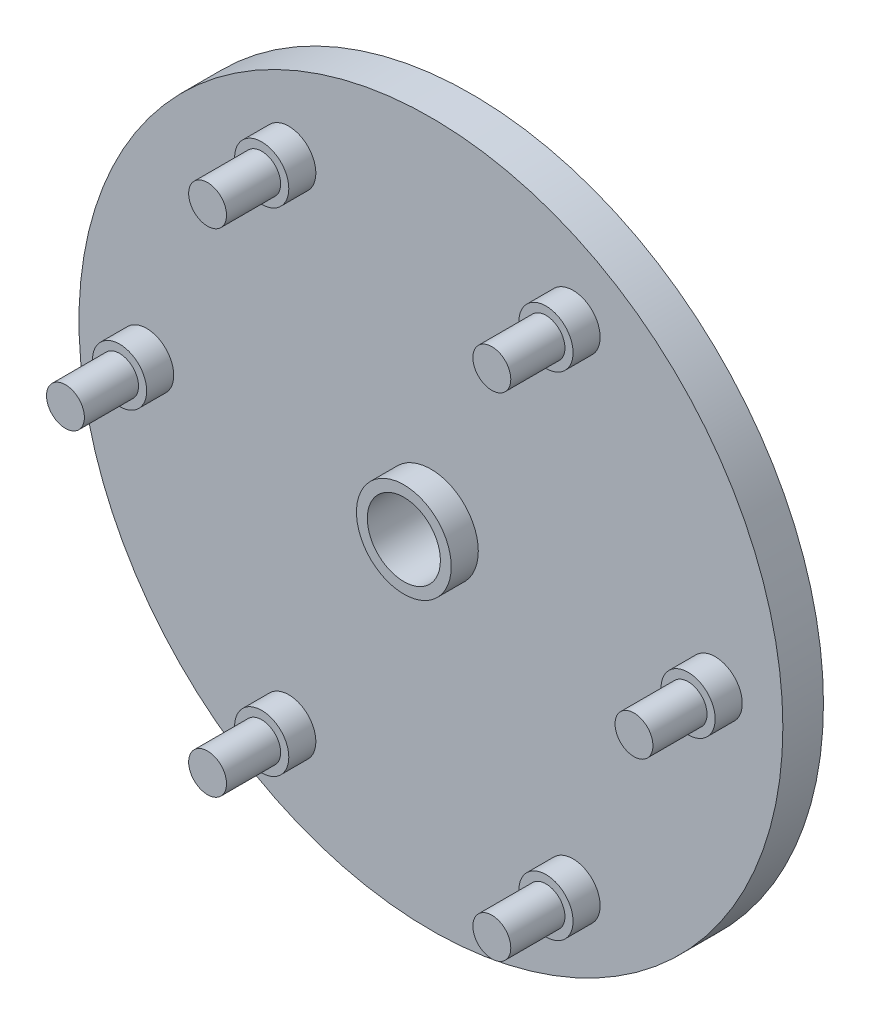
SolidWorks part; units mm, degrees
ref_plane "前视基准面" through (0, 0, 0) normal (0, 0, 1) x (1, 0, 0)
ref_plane "上视基准面" through (0, 0, 0) normal (0, 1, 0) x (1, 0, 0)
ref_plane "右视基准面" through (0, 0, 0) normal (1, 0, 0) x (0, 0, -1)
other "Configuration Table"
sketch "草图1" plane through (0, 0, 0) normal (0, 0, 1) x (1, 0, 0)
  circle A0 centre (0, 0) radius 26
  point P0 (0, 0)
  point P19 (0, 0)
  dimension "D1" = 52
extrude "凸台-拉伸1" add sketch "草图1" against normal blind 3 contours A0
sketch "草图2" plane through (0, 0, 0) normal (0, 0, 1) x (1, 0, 0)
  line L0 (0, 0) -> (-21, 0) construction
  circle A1 centre (-21, 0) radius 1.4
  circle A2 centre (-10.5, 18.1865) radius 1.4
  circle A3 centre (10.5, 18.1865) radius 1.4
  circle A4 centre (21, 0) radius 1.4
  circle A5 centre (10.5, -18.1865) radius 1.4
  circle A6 centre (-10.5, -18.1865) radius 1.4
  point P17 (0, 0)
  dimension "D1" = 2.8
  dimension "D2" = 21
  dimension "D3" = 6
extrude "凸台-拉伸2" add sketch "草图2" along normal blind 6
sketch "草图3" plane through (0, 0, 0) normal (0, 0, 1) x (1, 0, 0)
  circle A0 centre (0, 0) radius 7.5
  dimension "D1" = 15
extrude "凸台-拉伸3" [suppressed] add sketch "草图3" along normal blind 6
sketch "草图4" plane through (0, 0, 0) normal (0, 0, 1) x (1, 0, 0)
  circle A0 centre (-10.5, 18.1865) radius 2
  circle A1 centre (10.5, 18.1865) radius 2
  circle A2 centre (21, 0) radius 2
  circle A3 centre (10.5, -18.1865) radius 2
  circle A4 centre (-10.5, -18.1865) radius 2
  circle A5 centre (-21, 0) radius 2
  point P16 (0, 0)
  dimension "D1" = 4
  dimension "D2" = 6
extrude "凸台-拉伸4" add sketch "草图4" along normal blind 2
sketch "草图5" plane through (0, 0, 0) normal (0, 0, 1) x (1, 0, 0)
  circle A0 centre (0, 0) radius 6
  point P3 (-0.1136, 1.1435)
  point P4 (0, 0)
  dimension "D1" = 12
extrude "切除-拉伸1" cut sketch "草图5" against normal through all
sketch "草图7" plane through (0, 0, 0) normal (0, 0, 1) x (1, 0, 0)
  circle A0 centre (0, 0) radius 6
  point P3 (-0.1136, 1.1435)
  point P4 (0, 0)
  dimension "D1" = 12
extrude "拉伸-薄壁1" add sketch "草图7" against normal blind 8 thin thin type one direction reverse wall 3.3
sketch "草图8" plane through (0, 0, 0) normal (0, 0, 1) x (1, 0, 0)
  circle A0 centre (0, 0) radius 3.5
  point P3 (0, 0)
  dimension "D1" = 7
extrude "拉伸-薄壁2" add sketch "草图8" along normal blind 2 thin thin type one direction reverse wall 0.8
